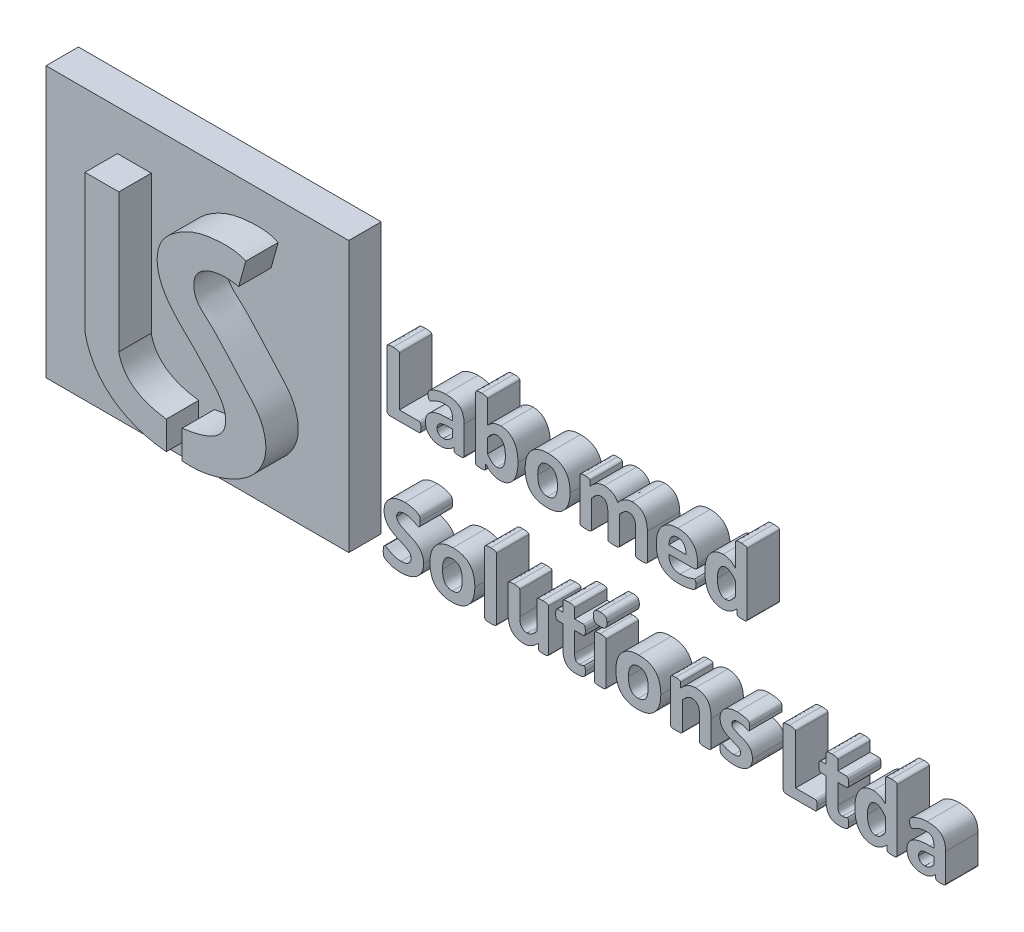
SolidWorks part; units mm, degrees
ref_plane "Plano frontal" through (0, 0, 0) normal (0, 0, 1) x (1, 0, 0)
ref_plane "Plano superior" through (0, 0, 0) normal (0, 1, 0) x (1, 0, 0)
ref_plane "Plano direito" through (0, 0, 0) normal (1, 0, 0) x (0, 0, -1)
sketch "Esboço1" plane through (0, 0, 0) normal (0, 0, 1) x (1, 0, 0)
  text T0 "<b>Labomed </b>\r\n<b>Solutions Ltda</b>" font "Calibri" height in points 22
extrude "Ressalto-extrusão1" add sketch "Esboço1" along normal blind 3
sketch "Esboço2" plane through (0, 0, 0) normal (0, 0, 1) x (1, 0, 0)
  line L1 (-29.5827, 16.5561) -> (-1.5774, 16.5561)
  line L2 (-29.5827, 16.5561) -> (-29.5827, -8.4439)
  line L3 (-29.5827, -8.4439) -> (-1.5774, -8.4439)
  line L4 (-1.5774, 16.5561) -> (-1.5774, -8.4439)
  dimension "D1" = 25
extrude "Ressalto-extrusão2" add sketch "Esboço2" along normal blind 3 separate body
sketch "Esboço3" plane through (0, 0, 3) normal (0, 0, 1) x (1, 0, 0)
  line L0 (-22.9765, 12.8178) -> (-19.8443, 12.8178)
  line L1 (-19.8443, 12.8178) -> (-19.8443, 0)
  line L2 (-22.9765, 12.8178) -> (-22.9765, 0)
  line L3 (-15.4592, -5.8073) -> (-15.4592, -3.1912)
  line L4 (-8.7624, 10.7701) -> (-8.1017, 13.1376)
  line L5 (-13.993, -3.1912) -> (-13.993, -5.8073)
  spline S0 degree 3 poles (-19.8443, 0) (-19.5543, -1.4412) (-18.4199, -2.8284) (-15.4592, -3.1912) knots 0 0 0 0 1 1 1 1
  spline S1 degree 3 poles (-22.9765, 0) (-22.343, -3.1194) (-19.6729, -5.4302) (-15.4592, -5.8073) knots 0 0 0 0 1 1 1 1
  spline S2 degree 3 poles (-13.993, -5.8073) (-11.984, -6.0543) (-7.9756, -4.8432) (-6.4169, -2.3463) (-6.1419, -0.4427) (-6.5784, 1.1246) (-8.6119, 3.4788) (-9.7375, 4.7076) (-11.5567, 6.6734) (-12.9516, 7.6098) (-13.0065, 9.7895) (-11.2133, 11.0081) (-9.3979, 10.9474) (-8.7624, 10.7701) knots 0 0 0 0 0.199547 0.300844 0.326269 0.428378 0.465296 0.658523 0.691498 0.770893 0.837393 0.898087 1 1 1 1
  spline S3 degree 3 poles (-8.1017, 13.1376) (-8.9248, 13.5189) (-10.3337, 13.5345) (-12.4694, 13.2847) (-14.3643, 12.4378) (-16.197, 10.896) (-16.4329, 8.5122) (-15.4103, 6.1856) (-13.2809, 4.2217) (-11.3572, 2.1704) (-9.8865, 0.3308) (-10.0232, -2.5895) (-12.9475, -3.0464) (-13.993, -3.1912) knots 0 0 0 0 0.095975 0.152802 0.233792 0.321873 0.398878 0.476755 0.59289 0.710882 0.789461 0.84063 1 1 1 1
extrude "Ressalto-extrusão3" add sketch "Esboço3" along normal blind 3
